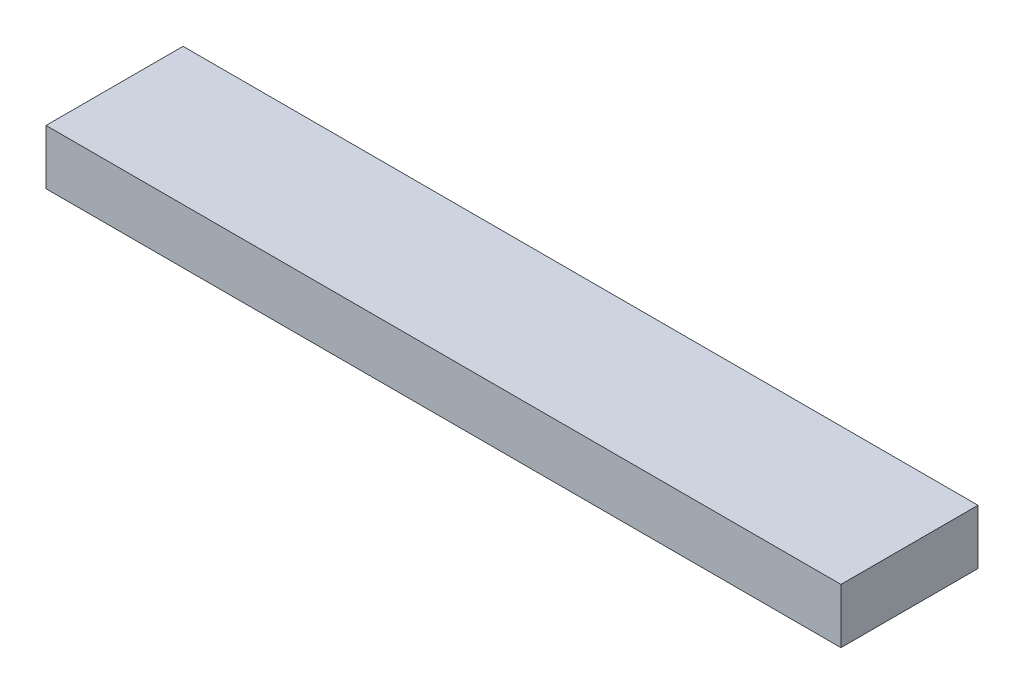
SolidWorks part; units mm, degrees
ref_plane "Front Plane" through (0, 0, 0) normal (0, 0, 1) x (1, 0, 0)
ref_plane "Top Plane" through (0, 0, 0) normal (0, 1, 0) x (1, 0, 0)
ref_plane "Right Plane" through (0, 0, 0) normal (1, 0, 0) x (0, 0, -1)
sketch "Sketch1" plane through (0, 0, 0) normal (0, 1, 0) x (1, 0, 0)
  line L7 (0, 0) -> (145, 0)
  line L8 (0, 0) -> (0, 25)
  line L9 (0, 25) -> (145, 25)
  line L10 (145, 0) -> (145, 25)
  point P0 (0, 0)
  dimension "D1" = 25
  dimension "D3" = 145
extrude "Boss-Extrude1" add sketch "Sketch1" along normal blind 10
